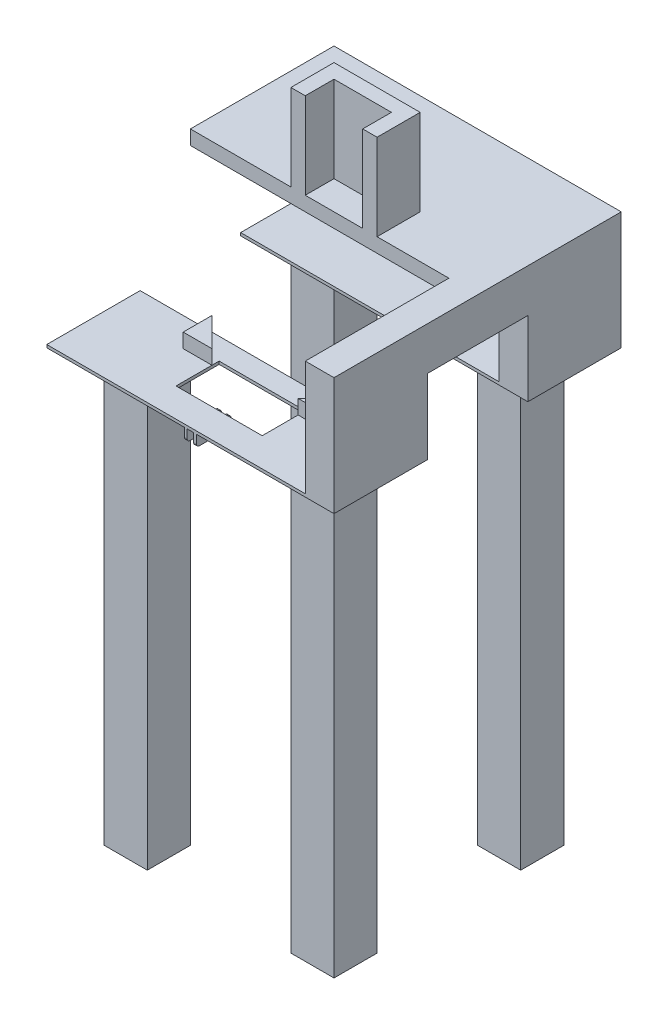
SolidWorks part; units mm, degrees
ref_plane "Front Plane" through (0, 0, 0) normal (0, 0, 1) x (1, 0, 0)
ref_plane "Top Plane" through (0, 0, 0) normal (0, 1, 0) x (1, 0, 0)
ref_plane "Right Plane" through (0, 0, 0) normal (1, 0, 0) x (0, 0, -1)
sketch "Sketch1" plane through (0, 0, 0) normal (0, 1, 0) x (1, 0, 0)
  line L1 (0, 0) -> (-1000, 0)
  line L2 (0, 0) -> (0, 1000)
  line L3 (0, 1000) -> (-1000, 1000)
  line L4 (-1000, 0) -> (-1000, 1000)
  dimension "D1" = 1000
  dimension "D2" = 1000
extrude "Boss-Extrude1" add sketch "Sketch1" along normal blind 10 contours L2 L1 L4 L3
sketch "Sketch5" plane through (0, 0, 0) normal (0, -1, 0) x (1, 0, 0)
  line L0 (-500, 619.3702) -> (-500, -1723.2419) construction
  line L1 (-1000, 0) -> (-1000, -1000) construction
  line L2 (-1658.8788, -500) -> (865.9105, -500) construction
  line L3 (0, 0) -> (-1000, 0) construction
  line L4 (-900, -750) -> (-750, -750)
  line L5 (-900, -100) -> (-750, -100)
  line L6 (-900, -100) -> (-900, -250)
  line L7 (-900, -250) -> (-750, -250)
  line L8 (-750, -100) -> (-750, -250)
  line L9 (-750, -900) -> (-750, -750)
  line L10 (-900, -900) -> (-750, -900)
  line L11 (-900, -900) -> (-900, -750)
  line L12 (-100, -900) -> (-100, -750)
  line L13 (-100, -900) -> (-250, -900)
  line L14 (-250, -900) -> (-250, -750)
  line L15 (-100, -750) -> (-250, -750)
  line L16 (-100, -250) -> (-250, -250)
  line L17 (-250, -100) -> (-250, -250)
  line L18 (-100, -100) -> (-250, -100)
  line L19 (-100, -100) -> (-100, -250)
  dimension "D1" = 500
  dimension "D2" = 500
  dimension "D3" = 150
  dimension "D4" = 150
  dimension "D5" = 100
  dimension "D6" = 100
extrude "Boss-Extrude2" add sketch "Sketch5" along normal blind 1500
sketch "Sketch7" plane through (0, 10, 0) normal (0, 1, 0) x (1, 0, 0)
  line L0 (0, 0) -> (0, 1000) construction
  line L1 (-650, 250) -> (-350, 250)
  line L2 (-650, 250) -> (-650, 100)
  line L3 (-650, 100) -> (-350, 100)
  line L4 (-350, 250) -> (-350, 100)
  line L5 (0, 0) -> (-1000, 0) construction
  point P6 (-500, 100)
  dimension "D1" = 300
  dimension "D2" = 150
  dimension "D3" = 500
  dimension "D4" = 100
extrude "Cut-Extrude1" cut sketch "Sketch7" against normal blind 1500 contours L2 L1 L4 L3
sketch "Sketch9" plane through (0, 0, 0) normal (0, -1, 0) x (1, 0, 0)
  line L0 (0, 0) -> (-1000, 0) construction
  line L1 (-521, 0) -> (-511, 0)
  line L2 (-521, 0) -> (-521, -120)
  line L3 (-521, -120) -> (-511, -120)
  line L4 (-511, 0) -> (-511, -120)
  line L5 (-1000, 0) -> (-1000, -1000) construction
  line L6 (0, 0) -> (0, -1000) construction
  line L7 (-489, 0) -> (-479, 0)
  line L8 (-489, 0) -> (-489, -120)
  line L9 (-489, -120) -> (-479, -120)
  line L10 (-479, 0) -> (-479, -120)
  dimension "D1" = 10
  dimension "D2" = 120
  dimension "D3" = 479
  dimension "D4" = 10
  dimension "D5" = 479
  dimension "D6" = 120
extrude "Boss-Extrude4" add sketch "Sketch9" along normal blind 40
fillet "Fillet1" radius 10 4 edges at (-484, -40, -120) (-516, -40, -120) (-484, 0, -120) (-516, 0, -120)
fillet "Fillet2" radius 10 2 edges at (-484, -40, 0) (-516, -40, 0)
sketch "Sketch10" plane through (-521, 0, 0) normal (-1, 0, 0) x (0, 0, 1)
  circle A0 centre (-110.2738, -30.1929) radius 5
  dimension "D1" = 10
extrude "Cut-Extrude3" cut sketch "Sketch10" against normal blind 55
sketch "Sketch11" plane through (0, 10, 0) normal (0, 1, 0) x (1, 0, 0)
  line L0 (0, 1000) -> (-1000, 1000) construction
  line L1 (-100, 1000) -> (0, 1000)
  line L2 (-100, 1000) -> (-100, 0)
  line L3 (-100, 0) -> (0, 0)
  line L4 (0, 1000) -> (0, 0)
  dimension "D1" = 100
extrude "Boss-Extrude5" add sketch "Sketch11" along normal blind 400
sketch "Sketch12" plane through (-100, 0, 0) normal (-1, 0, 0) x (0, 0, 1)
  line L0 (-1000, 410) -> (-1000, 10) construction
  line L1 (-1000, 360) -> (-500, 360)
  line L2 (-1000, 360) -> (-1000, 410)
  line L3 (-1000, 410) -> (-500, 410)
  line L4 (-500, 360) -> (-500, 410)
  line L5 (-1000, 410) -> (0, 410) construction
  dimension "D1" = 50
  dimension "D2" = 500
extrude "Boss-Extrude6" add sketch "Sketch12" along normal blind 900
sketch "Sketch14" plane through (0, 410, 0) normal (0, 1, 0) x (1, 0, 0)
  line L0 (-1000, 500) -> (-100, 500) construction
  line L1 (-650, 500) -> (-350, 500)
  line L2 (-650, 500) -> (-650, 650)
  line L3 (-650, 650) -> (-350, 650)
  line L4 (-350, 500) -> (-350, 650)
  line L5 (0, 0) -> (0, 1000) construction
  point P6 (-500, 500)
  dimension "D1" = 300
  dimension "D2" = 150
  dimension "D3" = 500
extrude "Boss-Extrude7" add sketch "Sketch14" along normal blind 300
sketch "Sketch15" plane through (0, 710, 0) normal (0, 1, 0) x (1, 0, 0)
  line L0 (-650, 500) -> (-350, 500) construction
  line L1 (-600, 500) -> (-400, 500)
  line L2 (-600, 500) -> (-600, 600)
  line L3 (-600, 600) -> (-400, 600)
  line L4 (-400, 500) -> (-400, 600)
  line L5 (-350, 500) -> (-350, 650) construction
  line L6 (-650, 650) -> (-650, 500) construction
  dimension "D1" = 50
  dimension "D2" = 50
  dimension "D3" = 100
extrude "Cut-Extrude4" cut sketch "Sketch15" against normal blind 300 contours L2 L1 L4 L3
sketch "Sketch8" plane through (0, 10, 0) normal (0, 1, 0) x (1, 0, 0)
  line L0 (-1000, 0) -> (-1000, 1000) construction
  line L1 (-1000, 675) -> (0, 675)
  line L2 (-1000, 675) -> (-1000, 325)
  line L3 (-1000, 325) -> (0, 325)
  line L4 (0, 675) -> (0, 325)
  line L5 (-100, 1000) -> (-1000, 1000) construction
  point P6 (-1000, 500)
  dimension "D1" = 500
  dimension "D2" = 350
  dimension "D3" = 1000
extrude "Cut-Extrude2" cut sketch "Sketch8" against normal through all
sketch "Sketch16" plane through (0, 0, 0) normal (1, 0, 0) x (0, 0, -1)
  line L1 (675, 10) -> (325, 10)
  line L2 (675, 10) -> (675, 260)
  line L3 (675, 260) -> (325, 260)
  line L4 (325, 10) -> (325, 260)
  dimension "D1" = 250
  dimension "D2" = 350
extrude "Cut-Extrude5" cut sketch "Sketch16" against normal through all
sketch "Sketch18" plane through (0, 10, 0) normal (0, 1, 0) x (1, 0, 0)
  line L0 (-750, 325) -> (-750, 225)
  line L1 (-750, 225) -> (-650, 225)
  line L2 (-650, 225) -> (-750, 325)
  line L3 (-350, 225) -> (-250, 225)
  line L4 (-250, 225) -> (-250, 325)
  line L5 (-250, 325) -> (-350, 225)
  line L6 (-1000, 325) -> (-100, 325) construction
  line L7 (-650, 250) -> (-650, 100) construction
  line L8 (-350, 250) -> (-350, 100) construction
  dimension "D1" = 100
  dimension "D2" = 100
  dimension "D3" = 100
  dimension "D4" = 100
extrude "Boss-Extrude8" add sketch "Sketch18" along normal blind 50
sketch "Sketch21" plane through (-287.5, 0, -287.5) normal (-0.7071, 0, -0.7071) x (-0.7071, 0, 0.7071)
  line L0 (-53.033, 60) -> (88.3883, 60) construction
  line L1 (88.3883, 60) -> (88.3883, 10) construction
  line L3 (-53.033, 10) -> (88.3883, 10) construction
  circle A0 centre (17.8883, 45) radius 7.5
  circle A1 centre (17.8883, 25) radius 7.5
  dimension "D1" = 15
  dimension "D2" = 15
  dimension "D3" = 70.5
  dimension "D4" = 15
  dimension "D5" = 70.5
extrude "Cut-Extrude7" cut sketch "Sketch21" against normal blind 50
sketch "Sketch22" plane through (-212.5, 0, 212.5) normal (0.7071, 0, -0.7071) x (-0.7071, 0, -0.7071)
  line L1 (618.7184, 60) -> (618.7184, 10) construction
  line L2 (618.7184, 60) -> (760.1398, 60) construction
  line L3 (618.7184, 10) -> (760.1398, 10) construction
  circle A0 centre (689.2184, 45) radius 7.5
  circle A1 centre (689.2184, 25) radius 7.5
  dimension "D1" = 15
  dimension "D4" = 15
  dimension "D2" = 70.5
  dimension "D3" = 15
  dimension "D5" = 15
  dimension "D6" = 70.5
extrude "Cut-Extrude8" cut sketch "Sketch22" against normal blind 50
